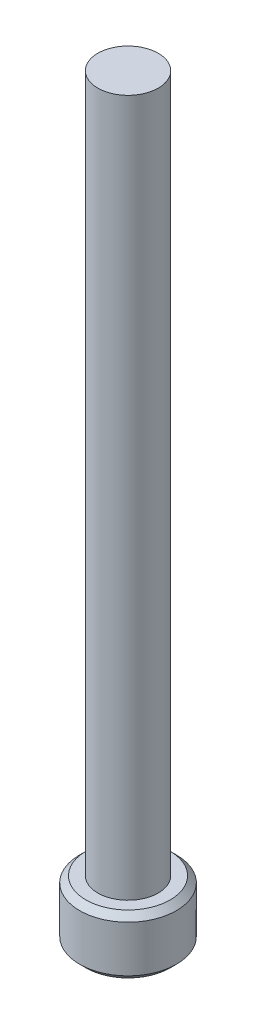
SolidWorks part; units mm, degrees
ref_plane "Front Plane" through (0, 0, 0) normal (0, 0, 1) x (1, 0, 0)
ref_plane "Top Plane" through (0, 0, 0) normal (0, 1, 0) x (1, 0, 0)
ref_plane "Right Plane" through (0, 0, 0) normal (1, 0, 0) x (0, 0, -1)
sketch "Sketch1" plane through (0, 0, 0) normal (0, 1, 0) x (1, 0, 0)
  circle A0 centre (0, 0) radius 2.4765
  dimension "D1" = 4.953
extrude "Boss-Extrude1" add sketch "Sketch1" along normal blind 57.15
sketch "Sketch2" plane through (0, 0, 0) normal (0, -1, 0) x (1, 0, 0)
  circle A0 centre (0, 0) radius 3.9624
  dimension "D1" = 7.9248
extrude "Boss-Extrude2" add sketch "Sketch2" along normal blind 4.826
sketch "Sketch3" plane through (0, -4.826, 0) normal (0, -1, 0) x (1, 0, 0)
  line L1 (2.2914, 0) -> (1.1457, 1.9844)
  line L2 (1.1457, 1.9844) -> (-1.1457, 1.9844)
  line L3 (-1.1457, 1.9844) -> (-2.2914, 0)
  line L4 (-2.2914, 0) -> (-1.1457, -1.9844)
  line L5 (-1.1457, -1.9844) -> (1.1457, -1.9844)
  line L6 (1.1457, -1.9844) -> (2.2914, 0)
  circle A0 centre (0, 0) radius 1.9844 construction
  dimension "D1" = 3.9688
extrude "Cut-Extrude1" cut sketch "Sketch3" against normal blind 2.286
chamfer "Chamfer1" distance 0.508 angle 45 2 edges at (0, -4.826, -3.9624) (0, 0, -3.9624)
